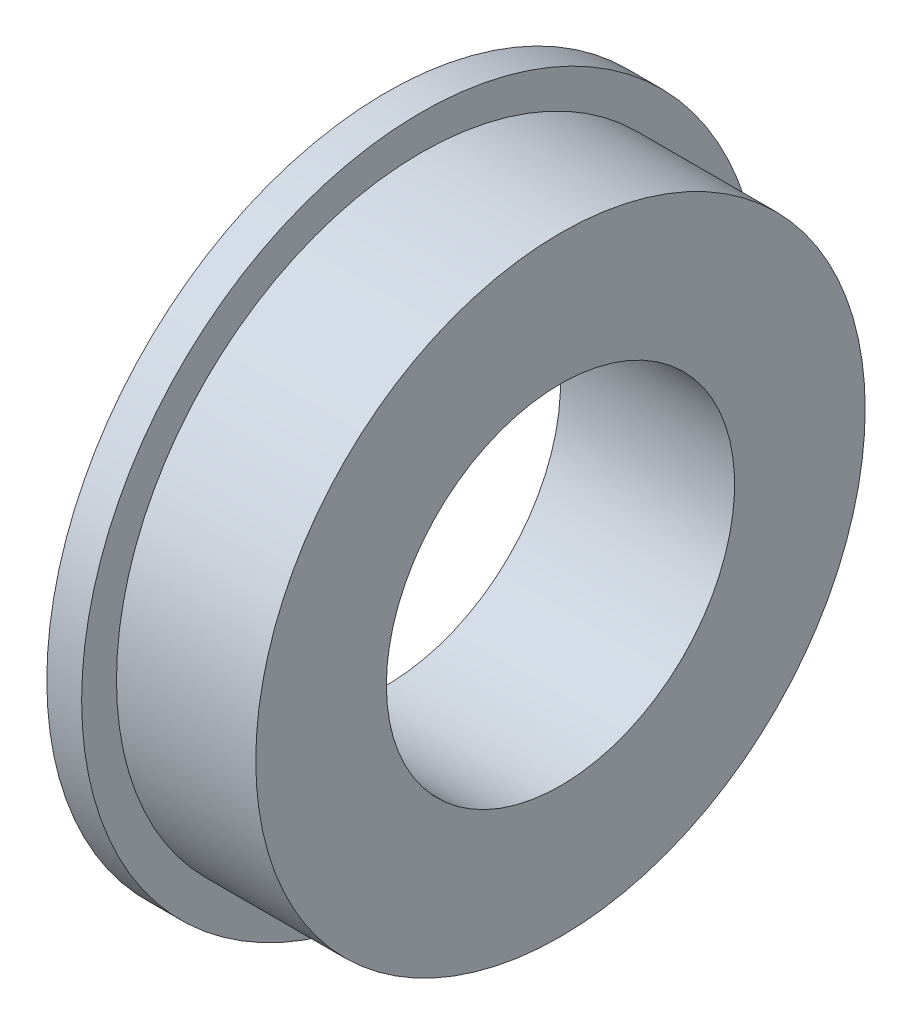
SolidWorks part; units mm, degrees
material "不锈钢 (铁素体)"
ref_plane "前视基准面" through (0, 0, 0) normal (0, 0, 1) x (1, 0, 0)
ref_plane "上视基准面" through (0, 0, 0) normal (0, 1, 0) x (1, 0, 0)
ref_plane "右视基准面" through (0, 0, 0) normal (1, 0, 0) x (0, 0, -1)
sketch "草图1" plane through (0, 0, 0) normal (0, 0, 1) x (1, 0, 0)
  line L0 (0, 0) -> (6.4842, 0) construction
  line L1 (0, 4) -> (0, 7.8)
  line L2 (0, 7.8) -> (0.8, 7.8)
  line L3 (0.8, 7.8) -> (0.8, 7)
  line L4 (0.8, 7) -> (4, 7)
  line L5 (4, 7) -> (4, 4)
  line L6 (4, 4) -> (0, 4)
  dimension "D1" = 8
  dimension "D2" = 14
  dimension "D3" = 15.6
  dimension "D4" = 0.8
  dimension "D5" = 4
revolve "旋转1" add sketch "草图1" angle 360 about L0
